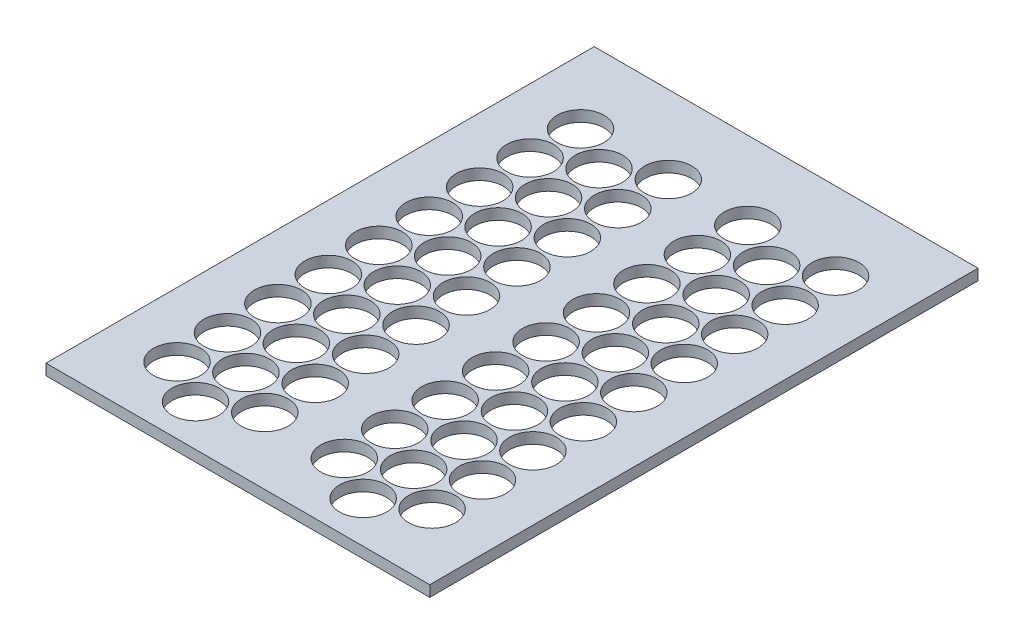
SolidWorks part; units mm, degrees
ref_plane "Front Plane" through (0, 0, 0) normal (0, 0, 1) x (1, 0, 0)
ref_plane "Top Plane" through (0, 0, 0) normal (0, 1, 0) x (1, 0, 0)
ref_plane "Right Plane" through (0, 0, 0) normal (1, 0, 0) x (0, 0, -1)
sketch "Sketch1" plane through (0, 0, 0) normal (0, 1, 0) x (1, 0, 0)
  line L0 (-88.9, 127) -> (-88.9, -127)
  line L1 (-88.9, 127) -> (88.9, 127)
  line L2 (-88.9, -127) -> (88.9, -127)
  line L3 (88.9, 127) -> (88.9, -127)
  line L4 (-88.9, 127) -> (88.9, -127) construction
  line L5 (-88.9, -127) -> (88.9, 127) construction
  line L6 (-59.075, 90.825) -> (-20.975, 90.825) construction
  line L7 (-20.975, 90.825) -> (-20.975, 68.828) construction
  line L8 (-20.975, 68.828) -> (-59.075, 90.825) construction
  line L9 (-59.075, 90.825) -> (-18.435, 90.825) construction
  line L10 (-59.075, 90.825) -> (-59.075, 67.457) construction
  line L11 (-59.075, -96.119) -> (-38.8377, -107.803) construction
  line L12 (0, 127) -> (0, -127) construction
  line L13 (88.9, 0) -> (-88.9, 0) construction
  circle A0 centre (-59.075, 90.825) radius 10.902
  circle A1 centre (-18.435, 90.825) radius 10.902
  circle A2 centre (-18.435, 67.457) radius 10.902
  circle A3 centre (-18.435, 44.089) radius 10.902
  circle A4 centre (-18.435, 20.721) radius 10.902
  circle A5 centre (-18.435, -2.647) radius 10.902
  circle A6 centre (-18.435, -26.015) radius 10.902
  circle A7 centre (-18.435, -49.383) radius 10.902
  circle A8 centre (-18.435, -72.751) radius 10.902
  circle A9 centre (-18.435, -96.119) radius 10.902
  circle A10 centre (-59.075, 67.457) radius 10.902
  circle A11 centre (-59.075, 44.089) radius 10.902
  circle A12 centre (-59.075, 20.721) radius 10.902
  circle A13 centre (-59.075, -2.647) radius 10.902
  circle A14 centre (-59.075, -26.015) radius 10.902
  circle A15 centre (-59.075, -49.383) radius 10.902
  circle A16 centre (-59.075, -72.751) radius 10.902
  circle A17 centre (-59.075, -96.119) radius 10.902
  circle A18 centre (-38.8377, -107.803) radius 10.902
  circle A19 centre (-38.8377, -84.435) radius 10.902
  circle A20 centre (-38.8377, -61.067) radius 10.902
  circle A21 centre (-38.8377, -37.699) radius 10.902
  circle A22 centre (-38.8377, -14.331) radius 10.902
  circle A23 centre (-38.8377, 9.037) radius 10.902
  circle A24 centre (-38.8377, 32.405) radius 10.902
  circle A25 centre (-38.8377, 55.773) radius 10.902
  circle A26 centre (-38.8377, 79.141) radius 10.902
  circle A27 centre (59.075, -96.119) radius 10.902
  circle A28 centre (18.435, -72.751) radius 10.902
  circle A29 centre (18.435, -96.119) radius 10.902
  circle A30 centre (38.8377, -84.435) radius 10.902
  circle A31 centre (38.8377, -107.803) radius 10.902
  circle A32 centre (59.075, -72.751) radius 10.902
  circle A33 centre (59.075, -49.383) radius 10.902
  circle A34 centre (38.8377, -61.067) radius 10.902
  circle A35 centre (18.435, -49.383) radius 10.902
  circle A36 centre (38.8377, -37.699) radius 10.902
  circle A37 centre (59.075, -26.015) radius 10.902
  circle A38 centre (18.435, -26.015) radius 10.902
  circle A39 centre (38.8377, -14.331) radius 10.902
  circle A40 centre (59.075, -2.647) radius 10.902
  circle A41 centre (18.435, -2.647) radius 10.902
  circle A42 centre (38.8377, 9.037) radius 10.902
  circle A43 centre (59.075, 20.721) radius 10.902
  circle A44 centre (18.435, 20.721) radius 10.902
  circle A45 centre (38.8377, 32.405) radius 10.902
  circle A46 centre (59.075, 44.089) radius 10.902
  circle A47 centre (18.435, 44.089) radius 10.902
  circle A48 centre (18.435, 67.457) radius 10.902
  circle A49 centre (38.8377, 55.773) radius 10.902
  circle A50 centre (59.075, 67.457) radius 10.902
  circle A51 centre (38.8377, 79.141) radius 10.902
  circle A52 centre (18.435, 90.825) radius 10.902
  circle A53 centre (59.075, 90.825) radius 10.902
  point P1 (0, 0)
  dimension "D3" = 21.804
  dimension "D1" = 254
  dimension "D2" = 177.8
  dimension "D7" = 29.825
  dimension "D8" = 36.175
  dimension "D4" = 38.1
  dimension "D5" = 60
  dimension "D10" = 40.64
  dimension "D11" = 23.368
  dimension "D13" = 23.368
  dimension "D6" = 2
  dimension "D9" = 9
  dimension "D12" = 2
extrude "Boss-Extrude1" add sketch "Sketch1" along normal blind 5.08
equation "\"SegLength\"= 10in"
equation "\"SegHeight\" = 7in"
equation "\"CellDiameter\"= 21.55mm"
equation "\"PocketTolerance\" = .01in"
equation "\"D1@Sketch1\"=\"SegLength\""
equation "\"D2@Sketch1\"=\"SegHeight\""
equation "\"D3@Sketch1\"=\"CellDiameter\" + \"PocketTolerance\""
equation "\"CellSpacing\"= 1mm"
equation "\"CellAngle\" = 30"
equation "\"SideBorder\"= .75"
equation "\"CellRadius\"= \"CellDiameter\" / 2"
equation "\"TopBorder\" = 1"
equation "\"D8@Sketch1\"=\"CellRadius\"+\"TopBorder\""
equation "\"D7@Sketch1\"=\"CellRadius\"+\"SideBorder\""
